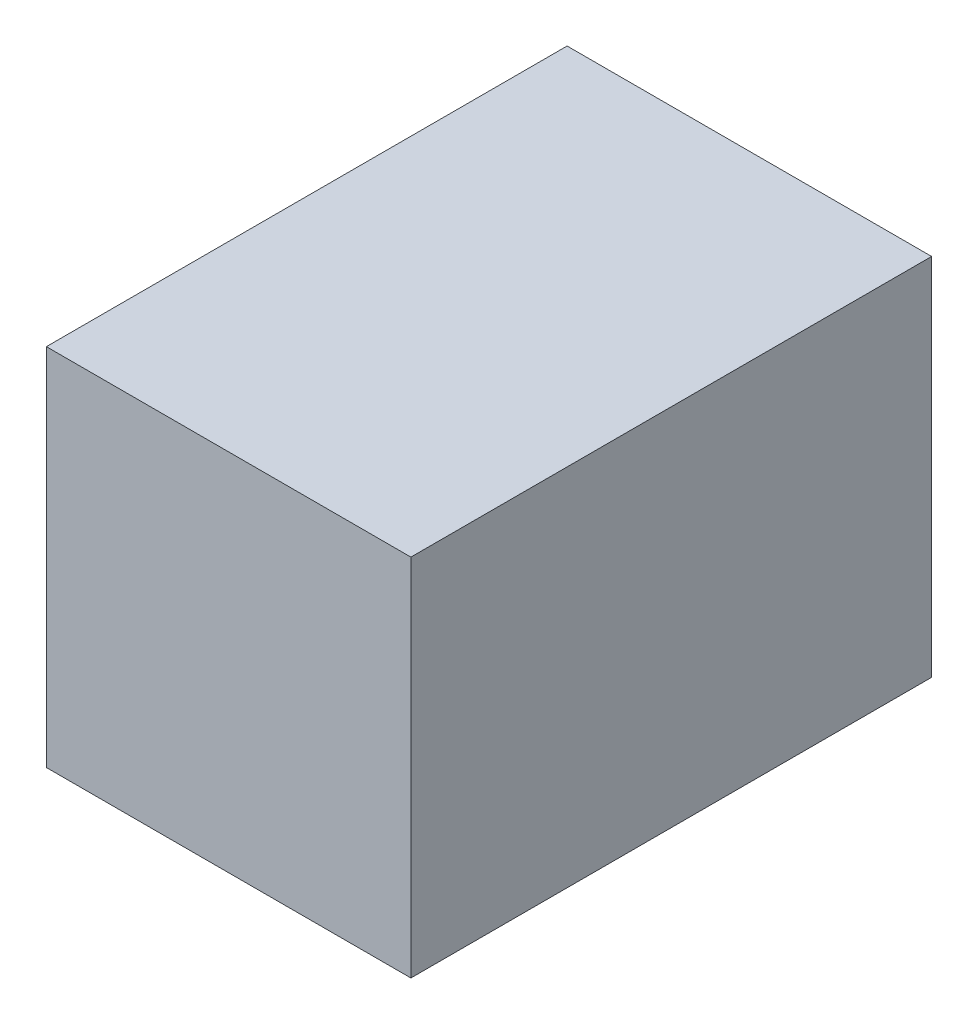
SolidWorks part; units mm, degrees
ref_plane "Plan de face" through (0, 0, 0) normal (0, 0, 1) x (1, 0, 0)
ref_plane "Plan de dessus" through (0, 0, 0) normal (0, 1, 0) x (1, 0, 0)
ref_plane "Plan de droite" through (0, 0, 0) normal (1, 0, 0) x (0, 0, -1)
sketch "Esquisse1" plane through (0, 0, 0) normal (0, 0, 1) x (1, 0, 0)
  line L1 (-17.5, 17.5) -> (17.5, 17.5)
  line L2 (-17.5, 17.5) -> (-17.5, -17.5)
  line L3 (-17.5, -17.5) -> (17.5, -17.5)
  line L4 (17.5, 17.5) -> (17.5, -17.5)
  line L5 (-17.5, 17.5) -> (17.5, -17.5) construction
  line L6 (-17.5, -17.5) -> (17.5, 17.5) construction
  point P0 (0, 0)
  dimension "D1" = 35
extrude "Boss.-Extru.1" add sketch "Esquisse1" along normal blind 50
